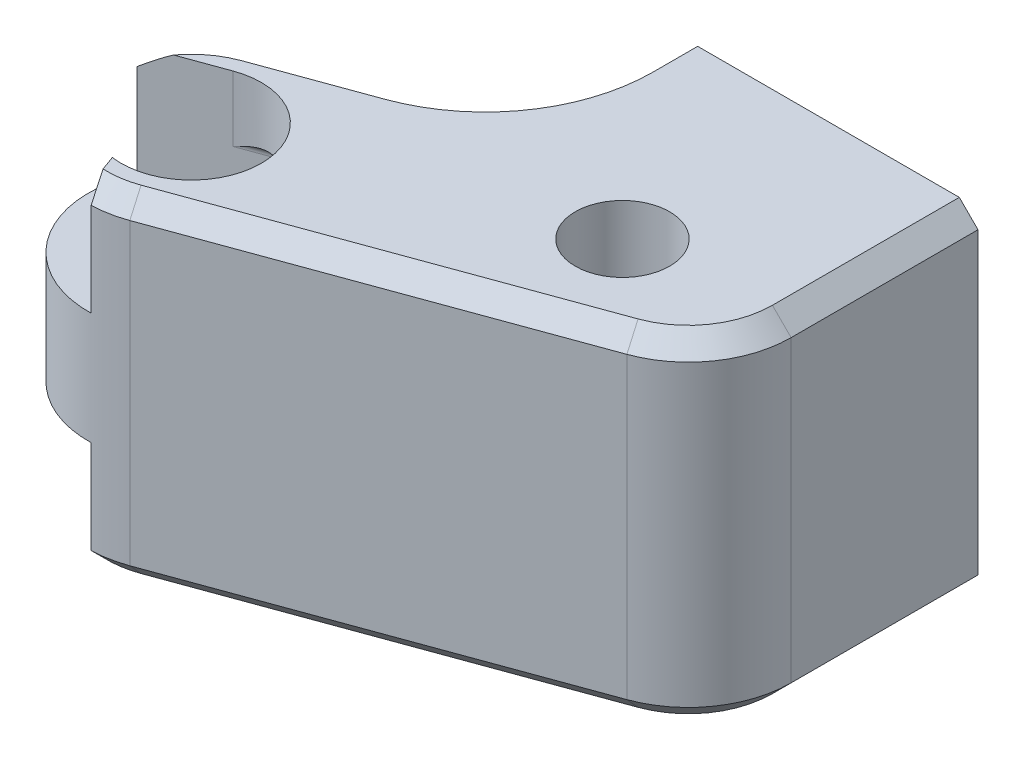
SolidWorks part; units mm, degrees
ref_plane "前视基准面" through (0, 0, 0) normal (0, 0, 1) x (1, 0, 0)
ref_plane "上视基准面" through (0, 0, 0) normal (0, 1, 0) x (1, 0, 0)
ref_plane "右视基准面" through (0, 0, 0) normal (1, 0, 0) x (0, 0, -1)
other "Configuration Table"
sketch "草图1" plane through (0, 0, 0) normal (0, 1, 0) x (1, 0, 0)
  line L0 (-36.8893, 0) -> (52.4222, 0) construction
  line L1 (-19.5, -7.0974) -> (0, 0) construction
  line L2 (-21.3811, -1.9291) -> (-10.5, 2.0313)
  line L3 (-17.6189, -12.2657) -> (1.8811, -5.1683)
  line L4 (5.5, 0) -> (5.5, 10)
  line L6 (-10.5, 10) -> (5.5, 10)
  line L7 (-10.5, 10) -> (-10.5, 2.0313)
  arc A0 (-21.3811, -1.9291) -> (-17.6189, -12.2657) centre (-19.5, -7.0974) ccw
  arc A1 (1.8811, -5.1683) -> (5.5, 0) centre (0, 0) ccw
  circle A2 centre (-19.5, -7.0974) radius 2.51
  circle A4 centre (-2.5855, -0.9411) radius 2.525
  point P5 (-11.2763, -4.1042)
  dimension "D4" = 5.02
  dimension "D5" = 5.05
  dimension "D9" = 5.5
  dimension "D10" = 5.5
  dimension "D1" = 20
  dimension "D2" = 25
  dimension "D3" = 10
  dimension "D6" = 16
  dimension "D8" = 18
extrude "凸台-拉伸1" add sketch "草图1" along normal blind 18
ref_plane "基准面1" through (0, 9, 0) normal (0, -1, 0) x (-1, 0, 0)
ref_plane "基准面3" through (0, 9, 0) normal (0, 1, 0) x (1, 0, 0)
sketch "草图11" plane through (0, 18, 0) normal (0, 1, 0) x (1, 0, 0)
  circle A1 centre (-19.5, -7.0974) radius 3.75
  dimension "D2" = 7.5
extrude "切除-拉伸5" cut sketch "草图11" against normal blind 6
fillet "圆角1" radius 8 1 edges at (-10.5, 9, -2.0313)
sketch "草图12" plane through (0, 0, -10) normal (0, 0, -1) x (-1, 0, 0)
  line L0 (-5.5, 9) -> (10.8582, 9) construction
  line L1 (-5.5, 18) -> (-5.5, 0) construction
  line L2 (10.8582, 18) -> (10.8582, 0) construction
  line L3 (10.5, 18) -> (10.5, 0) construction
  circle A0 centre (4.5, 9) radius 2
  dimension "D1" = 4
  dimension "D2" = 6
extrude "切除-拉伸6" cut sketch "草图12" against normal blind 7
chamfer "倒角1" distance 1 angle 45 14 edges at (5.5, 0, -5) (4.5053, 0, 3.1547) (-7.8689, 0, 8.717) (-11.9468, 0, -3.0443) (-24.6683, 0, 8.9785) (-18.5725, 0, 0.9069) (5.5, 18, -5) (4.5053, 18, 3.1547) (-7.8689, 18, 8.717) (-11.9468, 18, -3.0443) (-24.6683, 18, 8.9785) (-18.5725, 18, 0.9069) (-10.5, 0, -8.8165) (-10.5, 18, -8.8165)
sketch "草图15" plane through (0, 18, 0) normal (0, 1, 0) x (1, 0, 0)
  line L0 (-20.7826, -3.5736) -> (-28.3001, -6.3097)
  line L1 (-15.4218, -0.8243) -> (-21.0391, -2.8688) construction
  line L2 (-23.0238, -8.38) -> (-19.7628, -17.3395) construction
  line L4 (-17.9609, -11.326) -> (-17.6189, -12.2657) construction
  line L6 (-19.0068, -13.569) -> (-20.0101, -10.8126)
  line L8 (-28.3001, -6.3097) -> (-24.8799, -15.7067)
  line L9 (-24.8799, -15.7067) -> (-19.0068, -13.569)
  circle A0 centre (-19.5, -7.0974) radius 3.75 construction
  arc A1 (-20.7826, -3.5736) -> (-20.0101, -10.8126) centre (-19.5, -7.0974) ccw
  dimension "D1" = 2
  dimension "D2" = 10
  dimension "D3" = 8
extrude "切除-拉伸8" cut sketch "草图15" against normal blind 6
sketch "草图16" plane through (0, 18, 0) normal (0, 1, 0) x (1, 0, 0)
  circle A0 centre (-2.5855, -0.9411) radius 3.525
  dimension "D1" = 7.05
extrude "切除-拉伸9" [suppressed] cut sketch "草图16" against normal blind 17
sketch "草图18" plane through (0, 0, -10) normal (0, 0, -1) x (-1, 0, 0)
  line L0 (-5.5, 9) -> (10.8582, 9) construction
  line L3 (-5.5, 17) -> (-5.5, 1) construction
  line L8 (10.8582, 17) -> (10.8582, 1) construction
  circle A2 centre (-0.5, 13) radius 1.015
  circle A3 centre (-0.5, 5) radius 1.015
  dimension "D1" = 2.03
  dimension "D2" = 4
  dimension "D3" = 5
extrude "切除-拉伸10" cut sketch "草图18" against normal blind 4
sketch "草图19" plane through (-21.1445, 0, 7.696) normal (-0.9397, 0, 0.342) x (0.342, 0, 0.9397)
  line L0 (-3.75, 12) -> (-3.75, 17) construction
  line L1 (5.2142, 12) -> (-3.75, 12) construction
  line L2 (-3.25, 12) -> (-2.85, 12)
  line L3 (-3.75, 12.5) -> (-3.75, 14.5)
  line L4 (-3.25, 15) -> (-2.85, 15)
  line L5 (-2.35, 12.5) -> (-2.35, 14.5)
  arc A1 (-2.85, 12) -> (-2.35, 12.5) centre (-2.85, 12.5) ccw
  arc A2 (-2.35, 14.5) -> (-2.85, 15) centre (-2.85, 14.5) ccw
  arc A3 (-3.75, 14.5) -> (-3.25, 15) centre (-3.25, 14.5) cw
  arc A4 (-3.25, 12) -> (-3.75, 12.5) centre (-3.25, 12.5) cw
  point P7 (-2.35, 12)
  point P12 (-3.75, 15)
  point P15 (-3.75, 12)
  dimension "D1" = 3
  dimension "D3" = 0.5
  dimension "D2" = 1.4
extrude "切除-拉伸11" cut sketch "草图19" against normal blind 16
mirror "镜向3" about plane through (0, 9, 0) normal (0, -1, 0) of "切除-拉伸5", "切除-拉伸8", "切除-拉伸11"
hole_wizard "M5 螺纹孔1" positions "草图21" profile "草图22" tap size "M5" standard "GB"
sketch "草图21" plane through (0, 0, -10) normal (0, 0, -1) x (-1, 0, 0)
  point P0 (4.5, 9)
sketch "草图22" plane through (-4.5, 9, -10) normal (1, 0, 0) x (0, 1, 0)
  line L0 (0, 0) -> (0, 8.2618)
  line L1 (0, 8.2618) -> (2.1, 7)
  line L2 (2.1, 7) -> (2.1, 0)
  line L5 (2.1, 0) -> (0, 0)
  line L10 (0, 8.2618) -> (-2.1, 7) construction
  line L11 (0, -6.35) -> (0, 107.95) construction
  dimension "螺纹孔钻头直径" = 4.2
  dimension "螺纹孔钻头深度" = 7
  dimension "导头角度" = 118
cosmetic thread "孔螺蚊线1" parameters "D1"=10, "D2"=5
